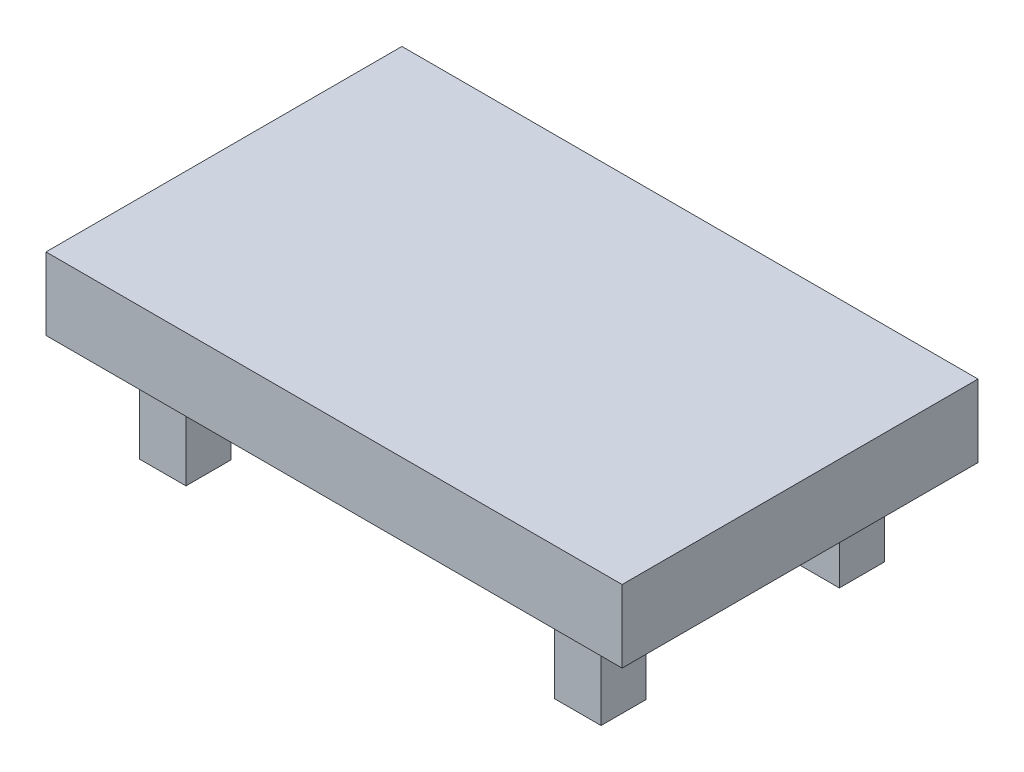
SolidWorks part; units mm, degrees
material "Chrome Stainless Steel"
ref_plane "Front Plane" through (0, 0, 0) normal (0, 0, 1) x (1, 0, 0)
ref_plane "Top Plane" through (0, 0, 0) normal (0, 1, 0) x (1, 0, 0)
ref_plane "Right Plane" through (0, 0, 0) normal (1, 0, 0) x (0, 0, -1)
sketch "Sketch1" plane through (0, 0, 0) normal (0, 1, 0) x (1, 0, 0)
  line L0 (0, 0) -> (1162.527, 0) construction
  line L1 (-1212.85, 749.3) -> (1212.85, 749.3)
  line L2 (-1212.85, 749.3) -> (-1212.85, -749.3)
  line L3 (-1212.85, -749.3) -> (1212.85, -749.3)
  line L4 (1212.85, 749.3) -> (1212.85, -749.3)
  line L5 (0, 132.506) -> (0, 1266.5562) construction
  point P4 (1212.85, 0)
  point P5 (0, -749.3)
  dimension "D1" = 2425.7
  dimension "D2" = 1498.6
extrude "Extrude1" add sketch "Sketch1" along normal blind 304.8
sketch "Sketch2" plane through (0, 0, 0) normal (0, -1, 0) x (1, 0, 0)
  line L0 (0, 749.3) -> (0, -749.3) construction
  line L1 (-1212.85, 749.3) -> (1212.85, 749.3) construction
  line L2 (1212.85, -749.3) -> (-1212.85, -749.3) construction
  line L3 (-1212.85, 0) -> (1212.85, 0) construction
  line L4 (-1212.85, -749.3) -> (-1212.85, 749.3) construction
  line L5 (1212.85, 749.3) -> (1212.85, -749.3) construction
  line L6 (776.0472, 596.8116) -> (776.0472, 406.6107)
  line L7 (-971.7449, 596.8116) -> (-776.0472, 596.8116)
  line L8 (-971.7449, 596.8116) -> (-971.7449, 406.6107)
  line L9 (-971.7449, 406.6107) -> (-776.0472, 406.6107)
  line L10 (-776.0472, 596.8116) -> (-776.0472, 406.6107)
  line L11 (971.7449, 406.6107) -> (776.0472, 406.6107)
  line L12 (971.7449, 596.8116) -> (971.7449, 406.6107)
  line L13 (971.7449, 596.8116) -> (776.0472, 596.8116)
  line L14 (-776.0472, -596.8116) -> (-776.0472, -406.6107)
  line L15 (-971.7449, -406.6107) -> (-776.0472, -406.6107)
  line L16 (-971.7449, -596.8116) -> (-971.7449, -406.6107)
  line L17 (-971.7449, -596.8116) -> (-776.0472, -596.8116)
  line L18 (971.7449, -596.8116) -> (776.0472, -596.8116)
  line L19 (971.7449, -596.8116) -> (971.7449, -406.6107)
  line L20 (971.7449, -406.6107) -> (776.0472, -406.6107)
  line L21 (776.0472, -596.8116) -> (776.0472, -406.6107)
  dimension "D1" = 190.201
  dimension "D2" = 195.6977
extrude "Extrude2" add sketch "Sketch2" along normal blind 406.4
hole_wizard "1/4-20 Tapped Hole1" [suppressed] positions "Sketch4" profile "Sketch3" tap size "1/4-20" standard "Ansi Inch"
sketch "Sketch4" plane through (0, 203.2, 0) normal (0, 1, 0) x (-1, 0, 0)
  point P1 (-103.8115, 1304.2597)
sketch "Sketch3" plane through (103.8115, 203.2, 1304.2597) normal (1, 0, 0) x (0, 0, 1)
  line L0 (0, 0) -> (0, 56.1438)
  line L1 (0, 56.1438) -> (2.5527, 54.61)
  line L2 (2.5527, 54.61) -> (2.5527, 0)
  line L5 (2.5527, 0) -> (0, 0)
  line L10 (0, 56.1438) -> (-2.5527, 54.61) construction
  line L11 (0, -6.35) -> (0, 107.95) construction
  dimension "Tap Drill Dia." = 5.1054
  dimension "Tap Drill Depth" = 54.61
  dimension "Drill Angle" = 118
cosmetic thread "Hole Thread1" [suppressed] parameters "D1"=50.8, "D2"=6.35
pattern_linear "LPattern1" [suppressed] count 50 spacing 25.4 count 85 spacing 25.4
